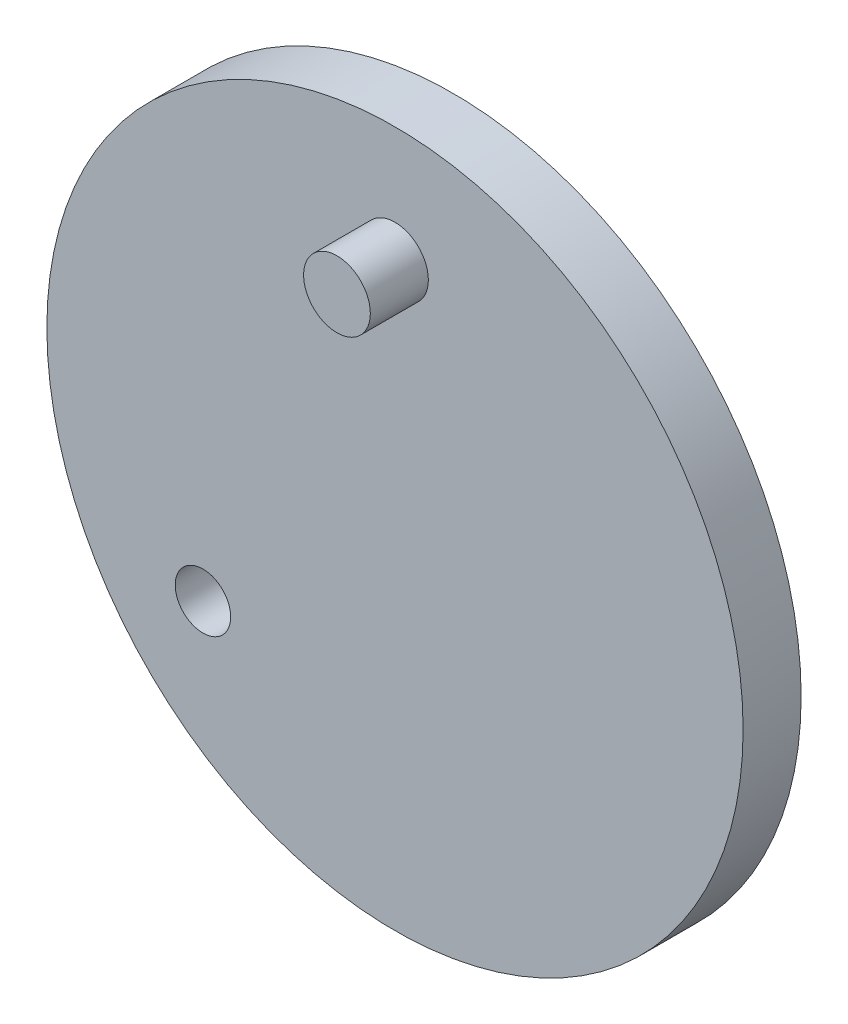
SolidWorks part; units mm, degrees
ref_plane "Front Plane" through (0, 0, 0) normal (0, 0, 1) x (1, 0, 0)
ref_plane "Top Plane" through (0, 0, 0) normal (0, 1, 0) x (1, 0, 0)
ref_plane "Right Plane" through (0, 0, 0) normal (1, 0, 0) x (0, 0, -1)
sketch "Sketch1" plane through (0, 0, 0) normal (0, 0, 1) x (1, 0, 0)
  circle A0 centre (0, 0) radius 30
extrude "Boss-Extrude1" add sketch "Sketch1" along normal blind 5
sketch "Sketch2" plane through (0, 0, 5) normal (0, 0, 1) x (1, 0, 0)
  circle A1 centre (0, 20) radius 2.875
extrude "Boss-Extrude2" add sketch "Sketch2" along normal blind 5 contours A1
sketch "Sketch3" plane through (0, 0, 5) normal (0, 0, 1) x (1, 0, 0)
  circle A0 centre (-16.5488, -13.6669) radius 2.3907
extrude "Cut-Extrude1" cut sketch "Sketch3" against normal blind 10
